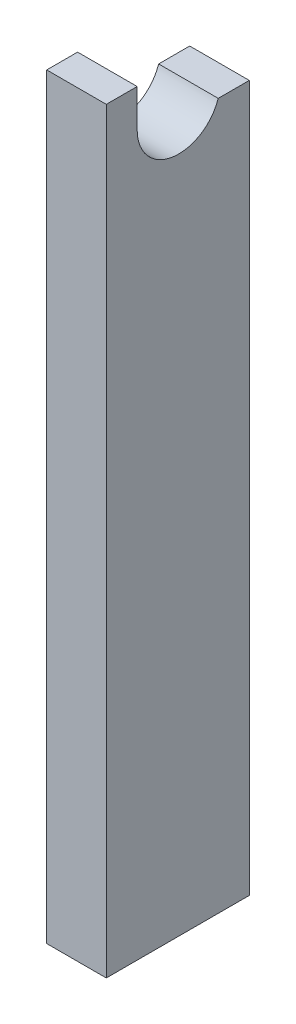
SolidWorks part; units mm, degrees
material "AISI Type A2 Tool Steel"
ref_plane "Front Plane" through (0, 0, 0) normal (0, 0, 1) x (1, 0, 0)
ref_plane "Top Plane" through (0, 0, 0) normal (0, 1, 0) x (1, 0, 0)
ref_plane "Right Plane" through (0, 0, 0) normal (1, 0, 0) x (0, 0, -1)
ref_plane "Plane1" through (-334.6667, 0, 0) normal (1, 0, 0) x (0, 0, -1)
sketch "Sketch1" plane through (-334.6667, 0, 0) normal (1, 0, 0) x (0, 0, -1)
  line L0 (-577.5453, -12.2879) -> (-565.5453, -12.2879)
  line L1 (-592.8969, -12.2879) -> (-442.8969, -12.2879) construction
  line L2 (-565.5453, -12.2879) -> (-565.5453, 35.7121)
  line L3 (-577.5453, -12.2879) -> (-577.5453, 51.2084)
  line L4 (-577.5453, 51.2084) -> (-574.9554, 51.2084)
  line L6 (-574.9554, 51.2084) -> (-574.9554, 48.0469)
  line L7 (-585.1937, 7.7121) -> (-557.8969, 7.7121) construction
  line L11 (-568.1526, 46.9467) -> (-565.5453, 46.9467)
  line L12 (-565.5453, 46.9467) -> (-565.5453, 35.7121)
  arc A3 (-574.9554, 48.0469) -> (-568.1526, 46.9467) centre (-571.465, 48.0469) ccw
  point P12 (-571.5453, 7.7121)
  point P15 (-585.1937, 7.7121)
  dimension "D1" = 12
  dimension "D2" = 6
extrude "Boss-Extrude1" add sketch "Sketch1" along normal blind 5
